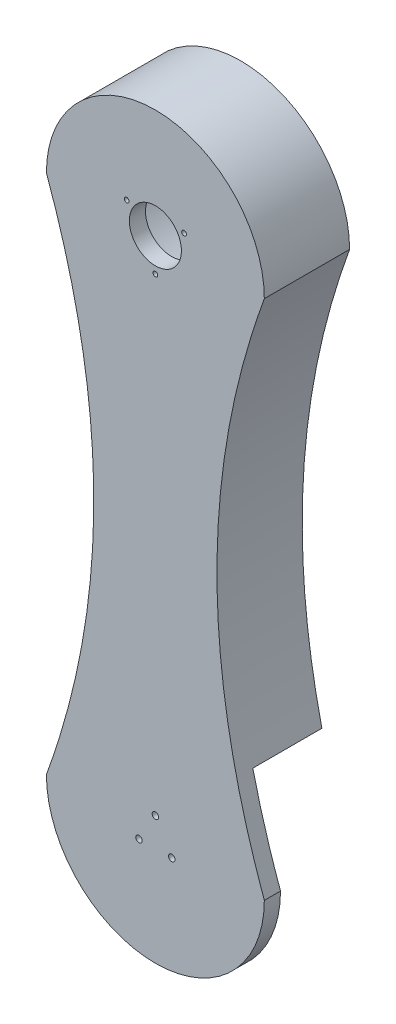
SolidWorks part; units mm, degrees
ref_plane "Front Plane" through (0, 0, 0) normal (1, 0, 0) x (0, 1, 0)
ref_plane "Top Plane" through (0, 0, 0) normal (0, 0, 1) x (0, 1, 0)
ref_plane "Right Plane" through (0, 0, 0) normal (0, 1, 0) x (-1, 0, 0)
sketch "Sketch1" plane through (0, 0, 0) normal (0, 0, 1) x (0, 1, 0)
  line L0 (0, 0) -> (550, 0) construction
  arc A0 (0, 115) -> (0, -115) centre (0, 0) ccw
  arc A1 (550, -115) -> (550, 115) centre (550, 0) ccw
  spline S0 degree 2 poles (0, 115) (275, 15) (550, 115) knots 0 0 0 1 1 1
  spline S1 degree 2 poles (0, -115) (275, -15) (550, -115) knots 0 0 0 1 1 1
  point P12 (275, 0)
  dimension "D1" = 230
  dimension "D2" = 550
  dimension "D3" = 130
extrude "Boss-Extrude1" add sketch "Sketch1" along normal blind 90
sketch "Sketch2" plane through (0, 0, 0) normal (0, 0, -1) x (1, 0, 0)
  circle A0 centre (0, 0) radius 97.5
  dimension "D1" = 195
extrude "Cut-Extrude1" cut sketch "Sketch2" against normal blind 72.91
sketch "Sketch6" plane through (0, 0, 0) normal (0, 0, -1) x (1, 0, 0)
  circle A0 centre (0, -550) radius 97.5
  circle A1 centre (0, 0) radius 97.5 construction
extrude "Cut-Extrude5" cut sketch "Sketch6" against normal blind 72.91
sketch "Sketch7" plane through (0, 0, 72.91) normal (0, 0, -1) x (1, 0, 0)
  circle A0 centre (0, -550) radius 27.5
  dimension "D1" = 55
extrude "Cut-Extrude6" cut sketch "Sketch7" against normal blind 72.91
sketch "Sketch10" plane through (0, 0, 0) normal (0, 0, -1) x (1, 0, 0)
  arc A1 (115, 0) -> (-115, 0) centre (0, 0) ccw construction
  arc A2 (115, 0) -> (-115, 0) centre (0, 0) ccw
  arc A3 (-85.7856, -97.6916) -> (85.7856, -97.6916) centre (0, 76.8839) ccw
  parabola Q0 (-115, -550) -> (-115, 0) focus (-443.125, -275) apex (-65, -275) construction
  parabola Q1 (-85.7856, -97.6916) -> (-115, 0) focus (-443.125, -275) apex (-65, -275)
  parabola Q2 (115, 0) -> (115, -550) focus (443.125, -275) apex (65, -275) construction
  parabola Q3 (115, 0) -> (85.7856, -97.6916) focus (443.125, -275) apex (65, -275)
  parabola Q4 (-115, -550) -> (-115, 0) focus (-443.125, -275) apex (-65, -275) construction
extrude "Cut-Extrude10" cut sketch "Sketch10" against normal up to surface (72.91 mm away) up to face at (-97.5, 0, 72.91)
sketch "Sketch13" plane through (0, 0, 72.91) normal (0, 0, -1) x (1, 0, 0)
  line L0 (0, 0) -> (0, -20) construction
  line L1 (0, 0) -> (-17.3205, 10) construction
  line L2 (0, 0) -> (17.3205, 10) construction
  circle A0 centre (0, -20) radius 3.4
  circle A1 centre (-17.3205, 10) radius 3.4
  circle A2 centre (17.3205, 10) radius 3.4
  dimension "D2" = 120
  dimension "D4" = 6.8
  dimension "D1" = 20
  dimension "D3" = 120
extrude "Cut-Extrude13" cut sketch "Sketch13" against normal up to surface (17.09 mm away) up to face at (-27.5, 550, 90)
sketch "Sketch14" plane through (0, 0, 90) normal (0, 0, 1) x (1, 0, 0)
  line L0 (0, 550) -> (0, 515) construction
  circle A0 centre (0, 515) radius 2.5
  dimension "D1" = 5
  dimension "D2" = 35
extrude "Cut-Extrude14" cut sketch "Sketch14" against normal up to surface (17.09 mm away) up to face at (-27.5, 550, 72.91)
pattern_circular "CirPattern1" count 3 every 120 about axis through (0, 550, 0) along (0, 0, 1) of "Cut-Extrude14"
